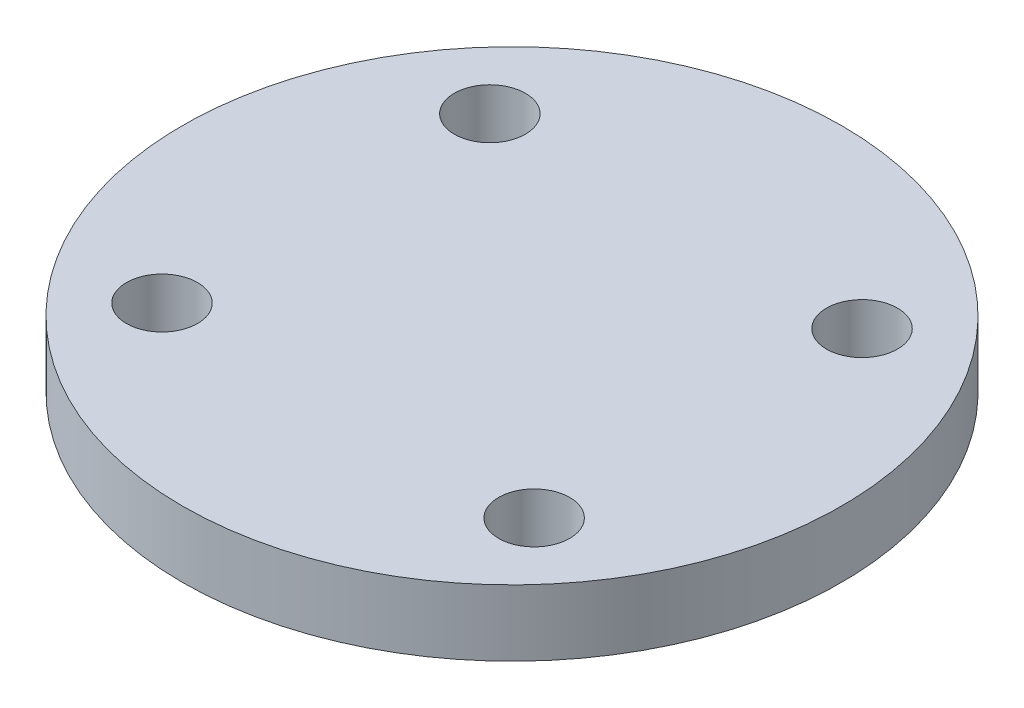
SolidWorks part; units mm, degrees
ref_plane "Front Plane" through (0, 0, 0) normal (0, 0, 1) x (1, 0, 0)
ref_plane "Top Plane" through (0, 0, 0) normal (0, 1, 0) x (1, 0, 0)
ref_plane "Right Plane" through (0, 0, 0) normal (1, 0, 0) x (0, 0, -1)
sketch "Sketch1" plane through (0, 0, 0) normal (0, 1, 0) x (1, 0, 0)
  circle A0 centre (0, 0) radius 19.9333
  circle A1 centre (11.2554, 9.9155) radius 2.15
  circle A2 centre (11.2554, -9.9155) radius 2.15
  circle A3 centre (-11.2554, -9.9155) radius 2.15
  circle A4 centre (-11.2554, 9.9155) radius 2.15
  dimension "D1" = 30
extrude "Boss-Extrude1" add sketch "Sketch1" along normal blind 4
sketch "Sketch2" plane through (0, 0, 0) normal (0, 1, 0) x (1, 0, 0)
  circle A0 centre (0, 0) radius 3
  circle A1 centre (0, 0) radius 5
